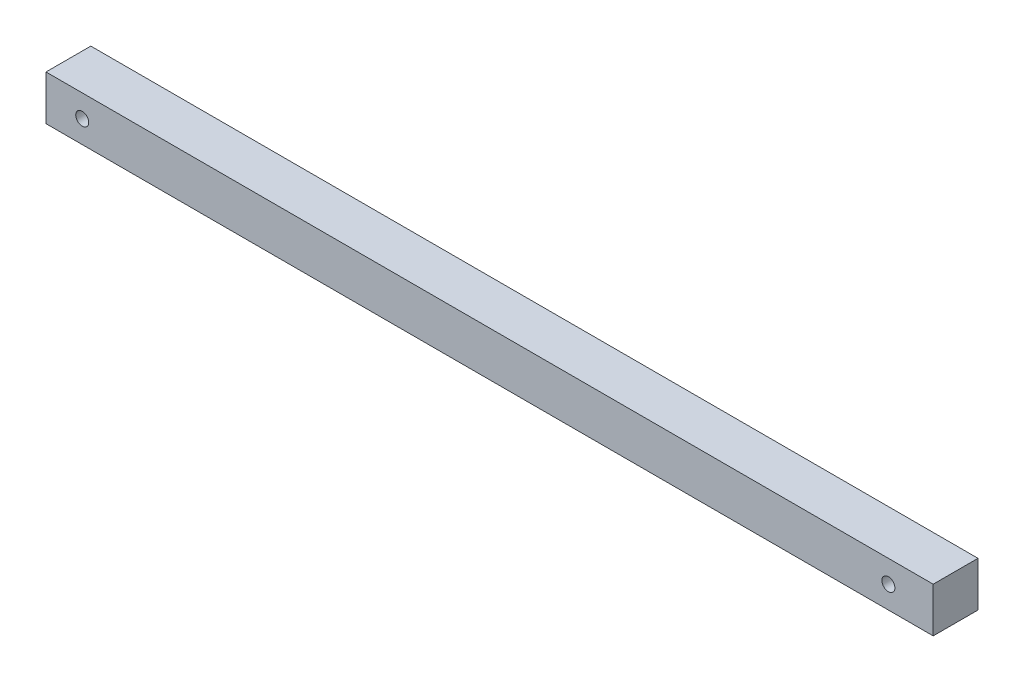
SolidWorks part; units mm, degrees
material "Nylon 101"
ref_plane "Front Plane" through (0, 0, 0) normal (0, 0, 1) x (1, 0, 0)
ref_plane "Top Plane" through (0, 0, 0) normal (0, 1, 0) x (1, 0, 0)
ref_plane "Right Plane" through (0, 0, 0) normal (1, 0, 0) x (0, 0, -1)
sketch "Sketch1" plane through (0, 0, 0) normal (0, 0, 1) x (1, 0, 0)
  line L1 (99, 5) -> (-99, 5)
  line L2 (99, 5) -> (99, -5)
  line L3 (99, -5) -> (-99, -5)
  line L4 (-99, 5) -> (-99, -5)
  line L5 (99, 5) -> (-99, -5) construction
  line L6 (99, -5) -> (-99, 5) construction
  point P0 (0, 0)
  dimension "D1" = 10
  dimension "D2" = 198
extrude "Boss-Extrude1" add sketch "Sketch1" along normal mid plane 10
hole_wizard "M2.5 Clearance Hole1" positions "Sketch2" profile "Sketch4" hole size "M2.5" standard "ANSI Metric" end condition through all
sketch "Sketch2" plane through (0, 0, -5) normal (0, 0, -1) x (-1, 0, 0)
  line L1 (-89, 0) -> (90.9182, 0) construction
  line L2 (-99, -5) -> (-99, 5) construction
  point P0 (-89, 0)
  point P3 (90.9182, 0)
  dimension "D1" = 179.9182
  dimension "D2" = 10
sketch "Sketch4" plane through (89, 0, -5) normal (1, 0, 0) x (0, 1, 0)
  line L0 (0, 0) -> (0, 10)
  line L1 (0, 10) -> (1.45, 10)
  line L2 (1.45, 10) -> (1.45, 0)
  line L5 (1.45, 0) -> (0, 0)
  line L11 (0, -6.35) -> (0, 107.95) construction
  dimension "Thru Hole Dia." = 2.9
  dimension "Thru Hole Depth" = 10
